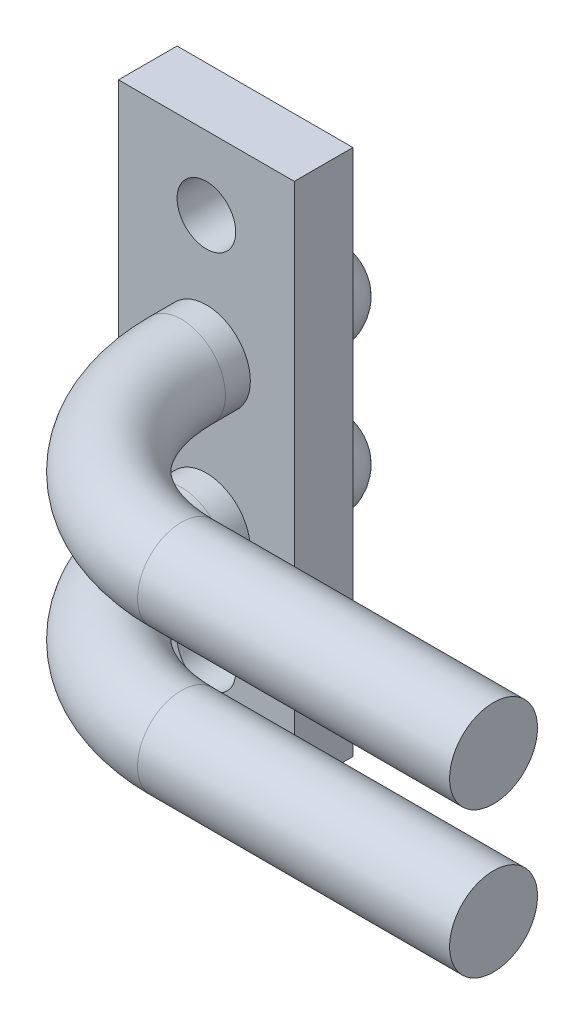
SolidWorks part; units mm, degrees
ref_plane "Front Plane" through (0, 0, 0) normal (0, 0, 1) x (1, 0, 0)
ref_plane "Top Plane" through (0, 0, 0) normal (0, 1, 0) x (1, 0, 0)
ref_plane "Right Plane" through (0, 0, 0) normal (1, 0, 0) x (0, 0, -1)
sketch "Sketch1" plane through (0, 0, 0) normal (0, 0, 1) x (1, 0, 0)
  line L1 (-3, -9) -> (3, -9)
  line L2 (-3, -9) -> (-3, 9)
  line L3 (-3, 9) -> (3, 9)
  line L4 (3, -9) -> (3, 9)
  line L5 (-3, -9) -> (3, 9) construction
  line L6 (-3, 9) -> (3, -9) construction
  point P0 (0, 0)
  dimension "D1" = 18
  dimension "D2" = 6
extrude "Boss-Extrude1" add sketch "Sketch1" along normal blind 2
sketch "Sketch2" plane through (0, 0, 0) normal (0, 0, -1) x (-1, 0, 0)
  circle A0 centre (0, 2.35) radius 1.5
  circle A1 centre (0, -2.62) radius 1.5
  dimension "D2" = 3
  dimension "D1" = 4.97
  dimension "D3" = 2.35
extrude "Boss-Extrude2" add sketch "Sketch2" along normal blind 3
fillet "Fillet1" radius 1.5 2 edges at (-1.5, -2.62, -3) (-1.5, 2.35, -3)
sketch "Sketch3" plane through (0, 0, 2) normal (0, 0, 1) x (1, 0, 0)
  circle A0 centre (0, -2.62) radius 1.5 construction
  circle A1 centre (0, 2.35) radius 1.5 construction
  circle A2 centre (0, -2.62) radius 1.5
  circle A3 centre (0, 2.35) radius 1.5
ref_plane "Plane1" through (0, 2.35, 0) normal (0, 1, 0) x (-1, 0, 0)
sketch "Sketch4" plane through (0, 2.35, 0) normal (0, 1, 0) x (-1, 0, 0)
  line L0 (0, 2) -> (0, 2.85)
  line L1 (1.5, 2) -> (-1.5, 2) construction
  line L2 (-6, 8.85) -> (-16.65, 8.85)
  arc A0 (0, 2.85) -> (-6, 8.85) centre (-6, 2.85) ccw
  point P8 (0, 8.85)
  dimension "D3" = 6
  dimension "D1" = 16.65
  dimension "D2" = 6.85
sweep "Sweep1" add profiles "Sketch3" path "Sketch4"
sketch "Sketch5" plane through (0, 0, 2) normal (0, 0, 1) x (1, 0, 0)
  line L0 (0, 0) -> (3, 0) construction
  line L1 (3, -9) -> (3, 9) construction
  line L2 (0, -6.5) -> (0, 6.5) construction
  line L3 (3, 9) -> (-3, 9) construction
  circle A0 centre (0, 6.5) radius 1
  circle A1 centre (0, -6.5) radius 1
  dimension "D1" = 2
  dimension "D2" = 2.5
extrude "Cut-Extrude1" cut sketch "Sketch5" against normal through all
